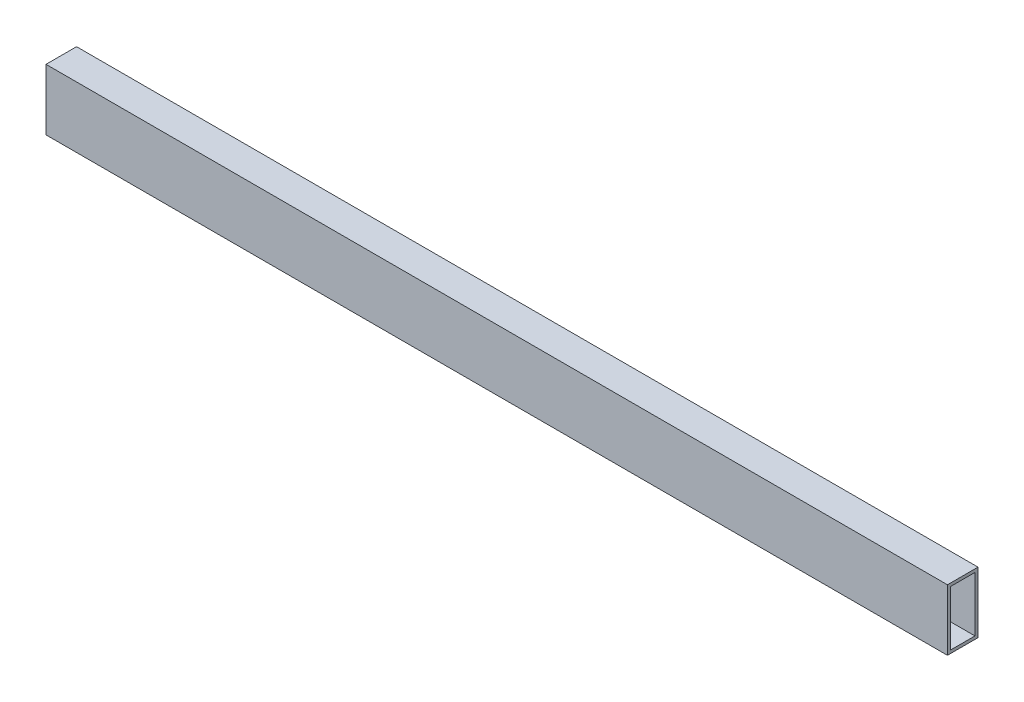
SolidWorks part; units mm, degrees
ref_plane "Plano frontal" through (0, 0, 0) normal (0, 0, 1) x (1, 0, 0)
ref_plane "Plano superior" through (0, 0, 0) normal (0, 1, 0) x (1, 0, 0)
ref_plane "Plano direito" through (0, 0, 0) normal (1, 0, 0) x (0, 0, -1)
sketch "Esboço1" plane through (0, 0, 0) normal (0, 1, 0) x (1, 0, 0)
  line L0 (0, 0) -> (590, 0)
  dimension "D1" = 590
sketch "Esboço2" plane through (0, 0, 0) normal (1, 0, 0) x (0, 0, -1)
  line L0 (-8, 18) -> (8, 18)
  line L1 (-10, -20) -> (10, -20)
  line L2 (-10, -20) -> (-10, 20)
  line L3 (-10, 20) -> (10, 20)
  line L4 (10, -20) -> (10, 20)
  line L5 (-10, -20) -> (10, 20) construction
  line L6 (-10, 20) -> (10, -20) construction
  line L7 (8, -18) -> (8, 18)
  line L8 (-8, -18) -> (8, -18)
  line L9 (-8, -18) -> (-8, 18)
  point P0 (0, 0)
  dimension "D1" = 20
  dimension "D2" = 40
  dimension "D3" = 2
sweep "Varredura1" add profiles "Esboço2" path "Esboço1"
